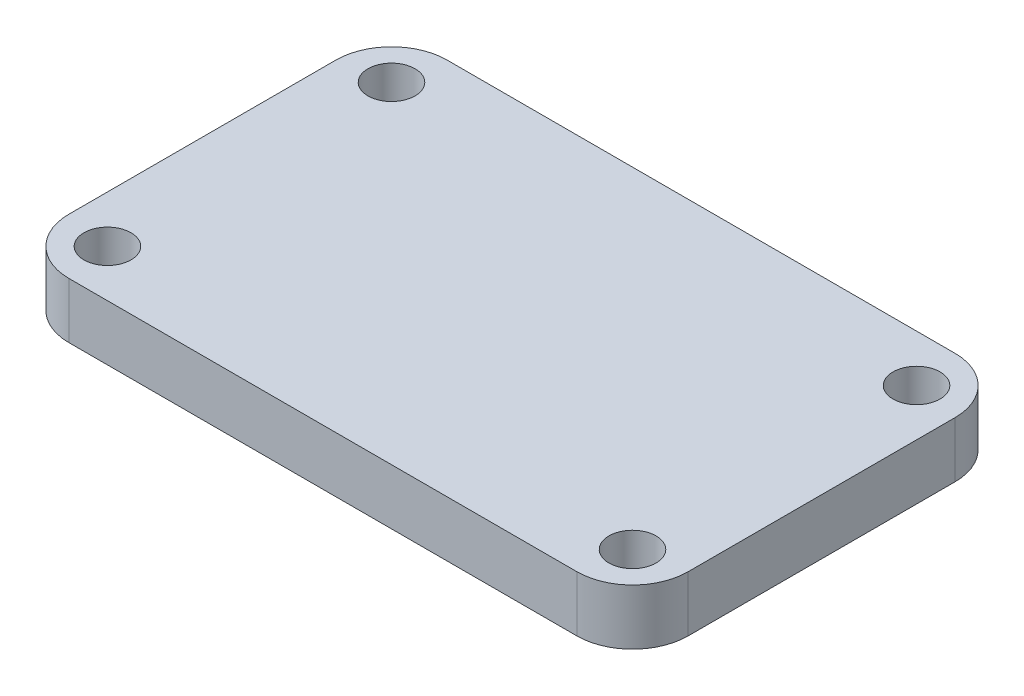
SolidWorks part; units mm, degrees
ref_plane "Front Plane" through (0, 0, 0) normal (0, 0, 1) x (1, 0, 0)
ref_plane "Top Plane" through (0, 0, 0) normal (0, 1, 0) x (1, 0, 0)
ref_plane "Right Plane" through (0, 0, 0) normal (1, 0, 0) x (0, 0, -1)
sketch "Sketch1" plane through (0, 0, 0) normal (0, 1, 0) x (1, 0, 0)
  line L0 (0, 0) -> (0, 20.4)
  line L1 (0, 20.4) -> (33.4, 20.4)
  line L2 (33.4, 20.4) -> (33.4, 0)
  line L3 (33.4, 0) -> (0, 0)
  dimension "D1" = 20.4
  dimension "D2" = 33.4
extrude "Boss-Extrude1" add sketch "Sketch1" along normal blind 3
sketch "Sketch4" plane through (0, 3, 0) normal (0, 1, 0) x (1, 0, 0)
  line L0 (0, 20.4) -> (2.54, 20.4)
  line L1 (33.4, 20.4) -> (0, 20.4) construction
  line L2 (2.54, 20.4) -> (2.54, 17.86)
  line L3 (0, 0) -> (2.54, 0)
  line L4 (2.54, 0) -> (2.54, 2.54)
  line L5 (33.4, 20.4) -> (30.86, 20.4)
  line L6 (30.86, 20.4) -> (30.86, 17.86)
  line L7 (33.4, 0) -> (30.86, 0)
  line L8 (30.86, 0) -> (30.86, 2.54)
  line L9 (0, 20.4) -> (0, 0) construction
  line L10 (0, 0) -> (33.4, 0) construction
  line L11 (33.4, 20.4) -> (0, 20.4) construction
  circle A0 centre (2.54, 17.86) radius 1.27
  circle A1 centre (2.54, 2.54) radius 1.27
  circle A2 centre (30.86, 17.86) radius 1.27
  circle A3 centre (30.86, 2.54) radius 1.27
  dimension "D1" = 2.54
  dimension "D9" = 2.54
  dimension "D10" = 2.54
  dimension "D11" = 2.54
  dimension "D12" = 2.54
  dimension "D2" = 2.54
  dimension "D3" = 2.54
  dimension "D4" = 2.54
  dimension "D5" = 2.54
  dimension "D6" = 2.54
  dimension "D7" = 2.54
  dimension "D8" = 2.54
extrude "Cut-Extrude1" cut sketch "Sketch4" against normal through all
fillet "Fillet5" radius 3 4 edges at (33.4, 1.5, 0) (33.4, 1.5, -20.4) (0, 1.5, -20.4) (0, 1.5, 0)
